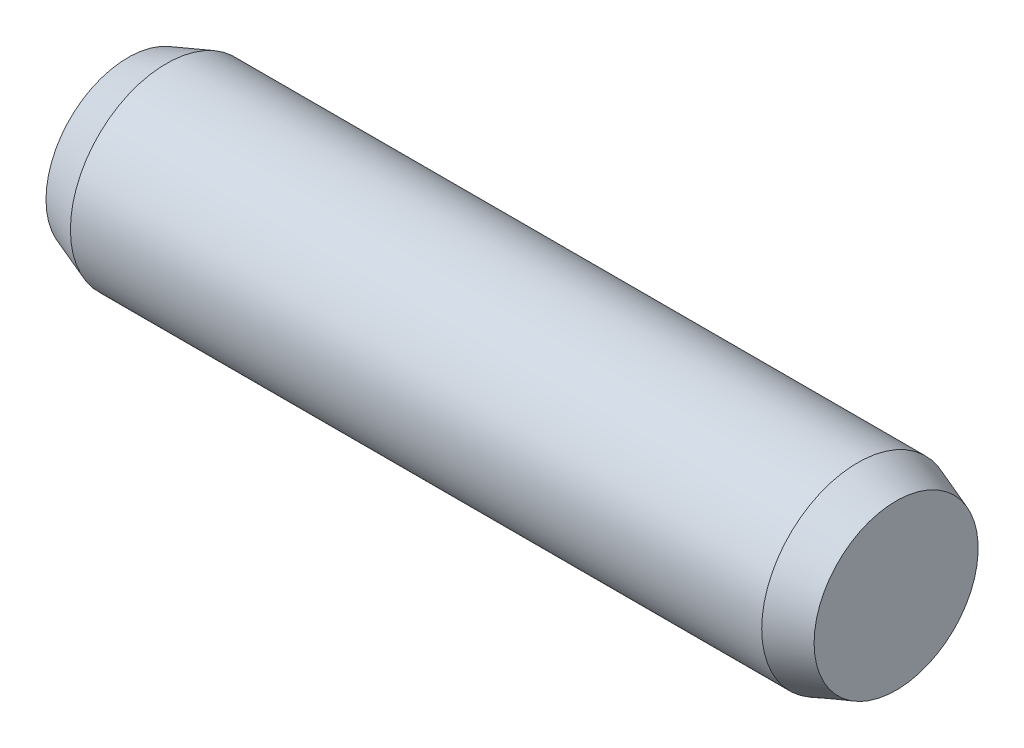
SolidWorks part; units mm, degrees
material "Простая углеродистая сталь"
ref_plane "Спереди" through (0, 0, 0) normal (0, 0, 1) x (1, 0, 0)
ref_plane "Сверху" through (0, 0, 0) normal (0, 1, 0) x (1, 0, 0)
ref_plane "Справа" through (0, 0, 0) normal (1, 0, 0) x (0, 0, -1)
sketch "Эскиз1" plane through (0, 0, 0) normal (0, 0, 1) x (1, 0, 0)
  line L0 (0, 0) -> (28.2589, 0) construction
  line L1 (0, 0) -> (0, 1.2816)
  line L2 (0, 1.2816) -> (0.6, 1.5)
  line L3 (0.6, 1.5) -> (11.4, 1.5)
  line L4 (11.4, 1.5) -> (12, 1.2816)
  line L5 (12, 1.2816) -> (12, 0)
  line L6 (12, 0) -> (0, 0)
  dimension "D1" = 3
  dimension "D2" = 20
  dimension "D3" = 0.6
  dimension "L" = 12
revolve "Повернуть1" add sketch "Эскиз1" angle 360 about L0
